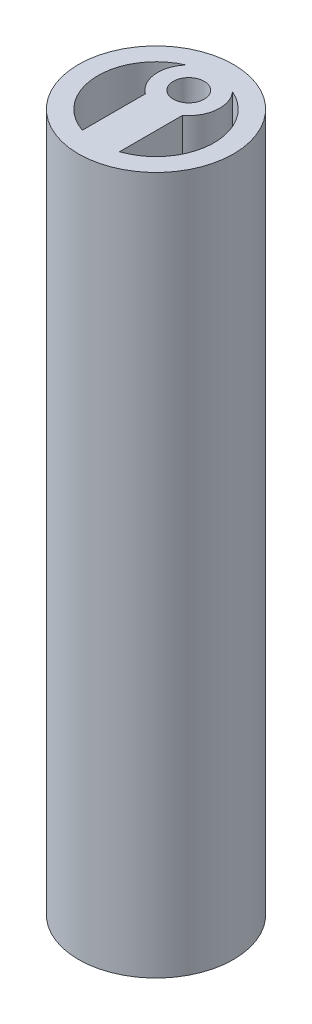
SolidWorks part; units mm, degrees
ref_plane "Front Plane" through (0, 0, 0) normal (0, 0, 1) x (1, 0, 0)
ref_plane "Top Plane" through (0, 0, 0) normal (0, 1, 0) x (1, 0, 0)
ref_plane "Right Plane" through (0, 0, 0) normal (1, 0, 0) x (0, 0, -1)
sketch "Sketch1" plane through (0, 0, 0) normal (0, 1, 0) x (1, 0, 0)
  circle A0 centre (0, 0) radius 5
  circle A1 centre (0, 0) radius 3.75
  dimension "D1" = 10
  dimension "D2" = 7.5
extrude "Boss-Extrude1" add sketch "Sketch1" along normal blind 45
sketch "Sketch3" plane through (0, 45, 0) normal (0, 1, 0) x (1, 0, 0)
  line L1 (-1.2, 4.3562) -> (1.2, 4.3562)
  line L2 (-1.2, 4.3562) -> (-1.2, -4.2333)
  line L3 (-1.2, -4.2333) -> (1.2, -4.2333)
  line L4 (1.2, 4.3562) -> (1.2, -4.2333)
  dimension "D1" = 1.2
  dimension "D2" = 1.2
extrude "Boss-Extrude3" add sketch "Sketch3" against normal through all
sketch "Sketch4" plane through (0, 45, 0) normal (0, 1, 0) x (1, 0, 0)
  circle A0 centre (0, 2.1134) radius 2
  point P2 (0, 3.9377)
  point P3 (0, 2.9749)
  dimension "D1" = 4
extrude "Boss-Extrude4" add sketch "Sketch4" against normal through all
sketch "Sketch5" plane through (0, 45, 0) normal (0, 1, 0) x (1, 0, 0)
  circle A0 centre (0, 2.1134) radius 1
  arc A1 (1.2, 0.5134) -> (1.499, 3.4374) centre (0, 2.1134) ccw construction
  dimension "D1" = 2
extrude "Cut-Extrude1" cut sketch "Sketch5" against normal through all
